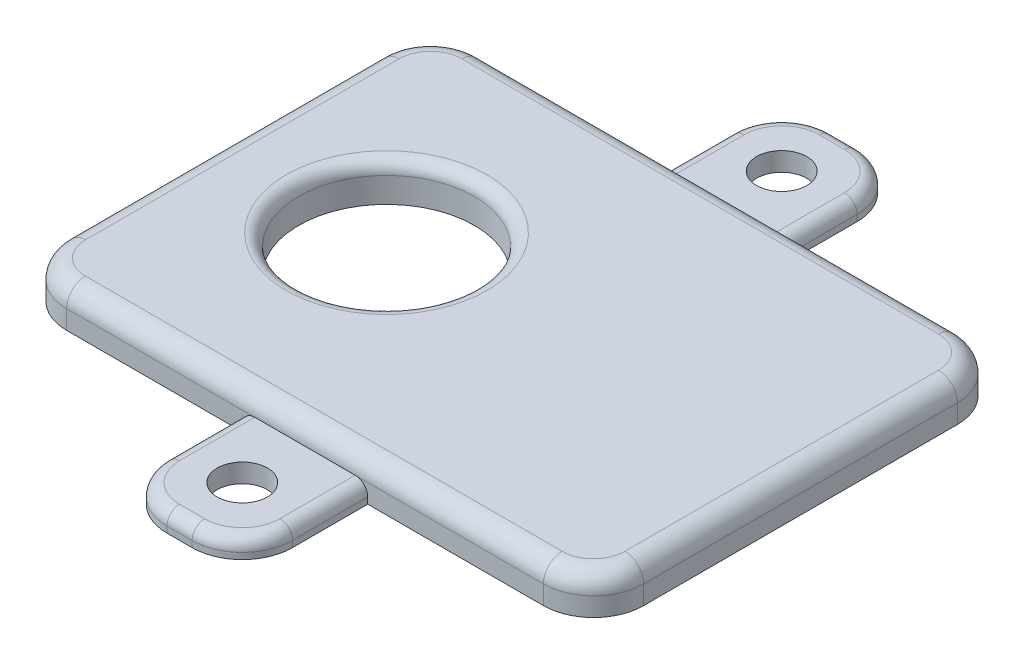
SolidWorks part; units mm, degrees
ref_plane "Front Plane" through (0, 0, 0) normal (0, 0, 1) x (1, 0, 0)
ref_plane "Top Plane" through (0, 0, 0) normal (0, 1, 0) x (1, 0, 0)
ref_plane "Right Plane" through (0, 0, 0) normal (1, 0, 0) x (0, 0, -1)
sketch "Base" plane through (0, 0, 0) normal (0, 1, 0) x (1, 0, 0)
  line L1 (-23, -16.5) -> (23, -16.5)
  line L2 (-23, -16.5) -> (-23, 16.5)
  line L3 (-23, 16.5) -> (23, 16.5)
  line L4 (23, -16.5) -> (23, 16.5)
  line L5 (-23, -16.5) -> (23, 16.5) construction
  line L6 (-23, 16.5) -> (23, -16.5) construction
  point P0 (0, 0)
  dimension "D1" = 33
  dimension "D2" = 46
extrude "Shell" add sketch "Base" along normal blind 3
sketch "Sketch2" plane through (0, 0, 16.5) normal (0, 0, 1) x (1, 0, 0)
  line L1 (-5, 0) -> (5, 0)
  line L2 (-5, 0) -> (-5, 1.5)
  line L3 (-5, 1.5) -> (5, 1.5)
  line L4 (5, 0) -> (5, 1.5)
  line L5 (-5, 0) -> (5, 1.5) construction
  line L6 (-5, 1.5) -> (5, 0) construction
  line L7 (-23, 0) -> (23, 0) construction
  point P0 (0, 0.75)
  point P5 (5, 3)
  point P6 (5.0876, 3)
  point P7 (0, 0)
  point P10 (5.0872, 2.4879)
  point P11 (-5, 2.7304)
  point P12 (0, 0)
  point P13 (-5, 1.3814)
  dimension "D1" = 10
  dimension "D2" = 1.5
extrude "Leg" add sketch "Sketch2" along normal blind 10
sketch "Sketch3" plane through (0, 3, 0) normal (0, 1, 0) x (1, 0, 0)
  line L0 (-5, -21.5) -> (5, -21.5) construction
  line L1 (-5, -26.5) -> (-5, -16.5) construction
  line L2 (5, -26.5) -> (5, -16.5) construction
  line L3 (0, -26.5) -> (0, -16.5) construction
  line L4 (5, -26.5) -> (-5, -26.5) construction
  circle A0 centre (0, -21.5) radius 2
  dimension "D1" = 4
extrude "Cut-Extrude1" cut sketch "Sketch3" against normal blind 10
fillet "Fillet1" radius 4 2 edges at (-5, 0.75, 26.5) (5, 0.75, 26.5)
mirror "Mirror3" about plane through (0, 0, 0) normal (0, 0, 1) of bodies 103
sketch "Sketch4" plane through (0, 3, 0) normal (0, 1, 0) x (1, 0, 0)
  line L0 (0, -16.5) -> (0, 16.5) construction
  line L1 (-23, -16.5) -> (23, -16.5) construction
  line L2 (23, 16.5) -> (-23, 16.5) construction
  line L3 (-23, 0) -> (23, 0) construction
  line L4 (-23, 16.5) -> (-23, -16.5) construction
  line L5 (23, -16.5) -> (23, 16.5) construction
  line L7 (-20, -13.5) -> (20, -13.5) construction
  line L8 (-20, -13.5) -> (-20, 13.5) construction
  line L9 (-20, 13.5) -> (20, 13.5) construction
  line L10 (20, -13.5) -> (20, 13.5) construction
  line L11 (-20, -13.5) -> (20, 13.5) construction
  line L12 (-20, 13.5) -> (20, -13.5) construction
  circle A0 centre (-10, 0) radius 7
  point P14 (0, 0)
  point P19 (20, 0)
  dimension "D1" = 14
  dimension "D2" = 40
  dimension "D3" = 27
  dimension "D4" = 30
extrude "Cut-Extrude2" cut sketch "Sketch4" against normal blind 10
fillet "Fillet2" radius 1 1 edges at (-10, 3, 7)
fillet "Fillet3" radius 4 4 edges at (23, 1.5, 16.5) (23, 1.5, -16.5) (-23, 1.5, -16.5) (-23, 1.5, 16.5)
fillet "Fillet10" radius 1.5 8 edges at (21.8284, 3, 15.3284) (0, 3, 16.5) (-21.8284, 3, 15.3284) (-23, 3, 0) (-21.8284, 3, -15.3284) (0, 3, -16.5) (21.8284, 3, -15.3284) (23, 3, 0)
fillet "Fillet11" radius 1 5 edges at (5, 1.5, 19.5) (3.8284, 1.5, 25.3284) (-5, 1.5, 19.5) (-3.8284, 1.5, 25.3284) (0, 1.5, 26.5)
fillet "Fillet12" radius 1 5 edges at (5, 1.5, -19.5) (3.8284, 1.5, -25.3284) (-5, 1.5, -19.5) (-3.8284, 1.5, -25.3284) (0, 1.5, -26.5)
equation "\"width\"= 2.7"
equation "\"height\"= 4.0"
equation "\"depthUp\"= 0.3"
equation "\"depthDown\"= 0.4"
equation "\"shellWidth\"= 0.6"
equation "\"shellHeight\"= 0.3"
equation "\"D2@Base\"= \"height\" + \"shellWidth\""
equation "\"D1@Base\"= \"width\" + \"shellWidth\""
equation "\"D1@Shell\" = \"shellHeight\""
equation "\"D1@ShellHole\" = \"height\" + 0.1"
equation "\"D1@Leg\" = 1.00cm"
